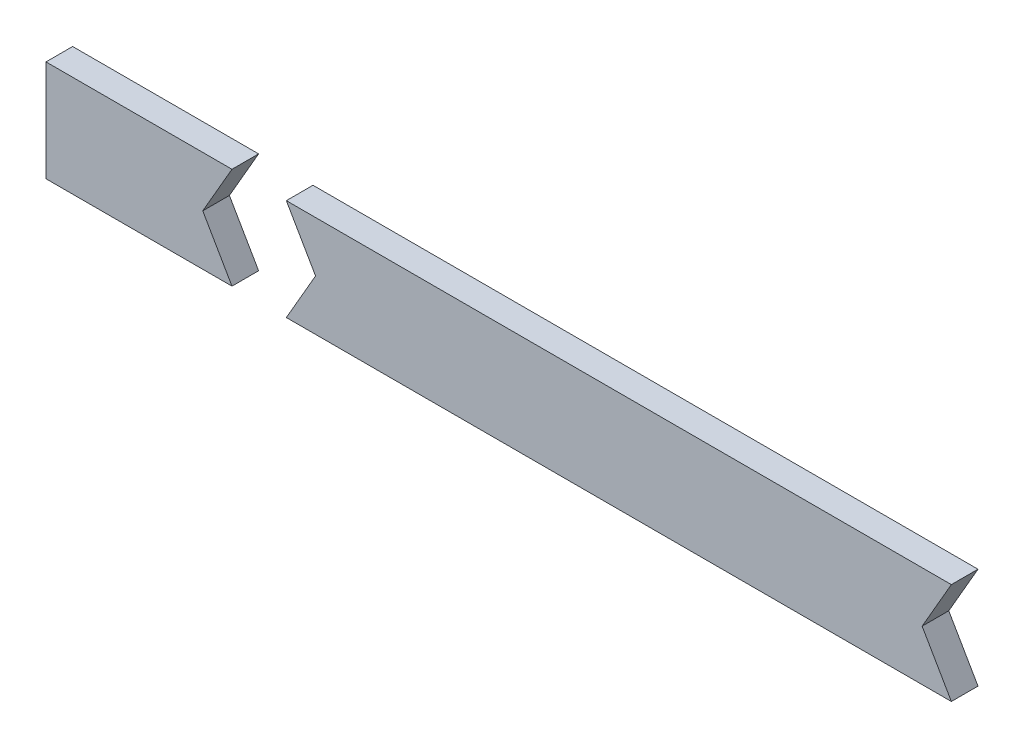
SolidWorks part; units mm, degrees
ref_plane "Front Plane" through (0, 0, 0) normal (0, 0, 1) x (1, 0, 0)
ref_plane "Top Plane" through (0, 0, 0) normal (0, 1, 0) x (1, 0, 0)
ref_plane "Right Plane" through (0, 0, 0) normal (1, 0, 0) x (0, 0, -1)
sketch "Sketch1" plane through (0, 0, 0) normal (0, 0, 1) x (1, 0, 0)
  line L0 (0, 0) -> (96.1257, 0) construction
  line L1 (55, 0) -> (-55, 0) construction
  line L2 (0, -54.6431) -> (0, 54.6431) construction
  line L3 (0, 2.85) -> (57, 2.85)
  line L4 (0, 2.85) -> (0, -2.85)
  line L5 (0, -2.85) -> (57, -2.85)
  line L6 (57, 2.85) -> (57, -2.85)
  line L8 (13.5877, 2.75) -> (10.4123, 2.75)
  line L9 (10.4123, 2.75) -> (8.8246, 0)
  line L10 (8.8246, 0) -> (10.4123, -2.75)
  line L11 (10.4123, -2.75) -> (13.5877, -2.75)
  line L12 (13.5877, -2.75) -> (15.1754, 0)
  line L13 (15.1754, 0) -> (13.5877, 2.75)
  line L14 (54.0877, 2.75) -> (50.9123, 2.75)
  line L15 (50.9123, 2.75) -> (49.3246, 0)
  line L16 (49.3246, 0) -> (50.9123, -2.75)
  line L17 (50.9123, -2.75) -> (54.0877, -2.75)
  line L18 (54.0877, -2.75) -> (55.6754, 0)
  line L19 (55.6754, 0) -> (54.0877, 2.75)
  circle A0 centre (12, 0) radius 2.75 construction
  circle A1 centre (52.5, 0) radius 2.75 construction
  dimension "D1" = 5.7
  dimension "D2" = 57
  dimension "D3" = 5.5
  dimension "D4" = 12
  dimension "D5" = 40.5
sketch "Sketch2" plane through (0, 0, 0) normal (0, 0, 1) x (1, 0, 0)
  line L0 (0, 2.85) -> (0, -2.85)
  line L1 (0, -2.85) -> (10.47, -2.85)
  line L2 (0, -2.85) -> (57, -2.85) construction
  line L3 (10.47, -2.85) -> (8.8246, 0)
  line L4 (8.8246, 0) -> (10.47, 2.85)
  line L5 (0, 2.85) -> (57, 2.85) construction
  line L6 (10.47, 2.85) -> (0, 2.85)
extrude "Boss-Extrude1" add sketch "Sketch2" along normal blind 1.5
sketch "Sketch3" plane through (0, 0, 0) normal (0, 0, 1) x (1, 0, 0)
  line L0 (13.53, 2.85) -> (15.1754, 0)
  line L1 (0, 2.85) -> (57, 2.85) construction
  line L2 (15.1754, 0) -> (13.53, -2.85)
  line L3 (0, -2.85) -> (57, -2.85) construction
  line L4 (13.53, -2.85) -> (50.97, -2.85)
  line L5 (50.97, -2.85) -> (49.3246, 0)
  line L6 (0, 0) -> (96.1257, 0) construction
  line L7 (49.3246, 0) -> (50.97, 2.85)
  line L8 (50.97, 2.85) -> (13.53, 2.85)
extrude "Boss-Extrude2" add sketch "Sketch3" along normal up to surface (1.5 mm away) separate body up to face at (5.9529, 0, 1.5)
